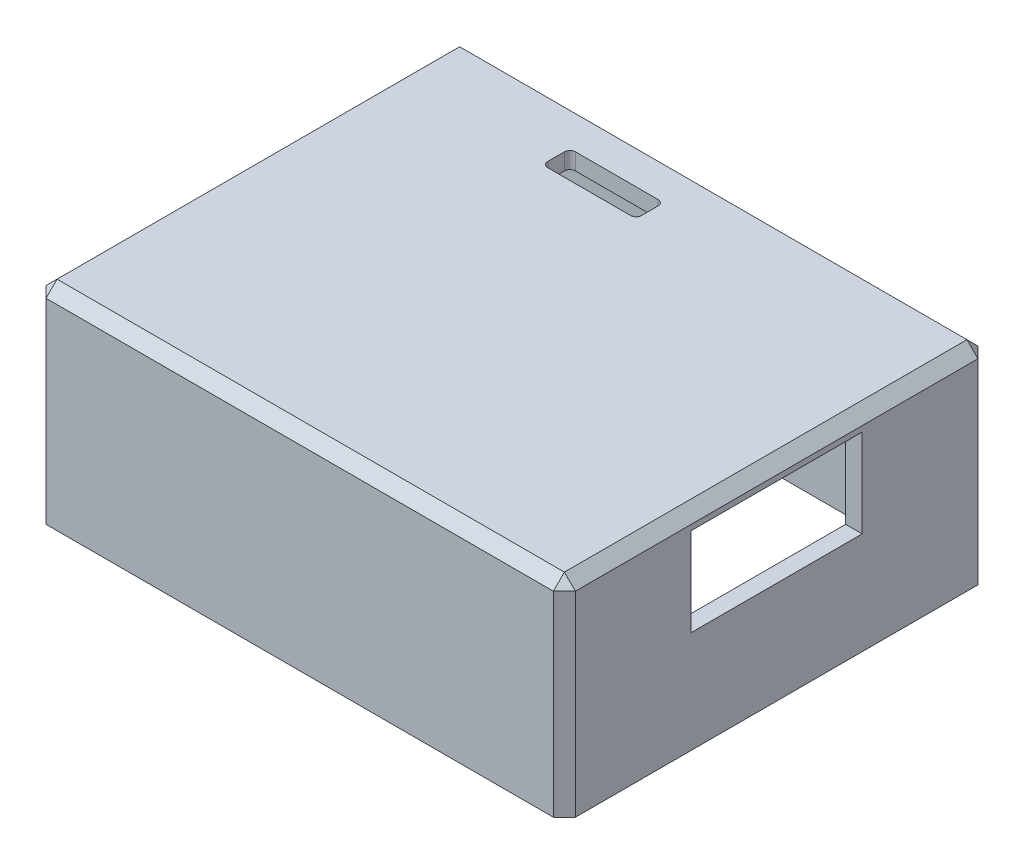
SolidWorks part; units mm, degrees
material "6061 Alloy"
ref_plane "Front Plane" through (0, 0, 0) normal (0, 0, 1) x (1, 0, 0)
ref_plane "Top Plane" through (0, 0, 0) normal (0, 1, 0) x (1, 0, 0)
ref_plane "Right Plane" through (0, 0, 0) normal (1, 0, 0) x (0, 0, -1)
sketch "Sketch1" plane through (0, 0, 0) normal (0, 1, 0) x (1, 0, 0)
  line L1 (0, 0) -> (22.86, 0)
  line L2 (0, 0) -> (0, 18.034)
  line L3 (0, 18.034) -> (22.86, 18.034)
  line L4 (22.86, 0) -> (22.86, 18.034)
  dimension "D1" = 22.86
  dimension "D2" = 18.034
sketch "Sketch2" plane through (0, 0, 0) normal (0, 1, 0) x (1, 0, 0)
  line L1 (-0.762, -0.762) -> (23.622, -0.762)
  line L2 (-0.762, -0.762) -> (-0.762, 18.796)
  line L3 (-0.762, 18.796) -> (23.622, 18.796)
  line L4 (23.622, -0.762) -> (23.622, 18.796)
  line L5 (-0.762, 18.796) -> (23.622, -0.762) construction
  line L6 (0, 0) -> (22.86, 18.034) construction
  line L7 (22.86, 18.034) -> (23.622, 18.034) construction
  line L8 (22.86, 18.034) -> (22.86, 18.796) construction
  line L9 (0, 18.034) -> (22.86, 18.034) construction
  point P10 (11.43, 9.017)
  point P11 (11.43, 9.017)
  dimension "D1" = 0.762
extrude "Boss-Extrude1" add sketch "Sketch2" along normal blind 6.477
extrude "Cut-Extrude1" cut sketch "Sketch1" along normal offset from surface (5.715 mm away) 0.762 up to face at (11.43, 6.477, -9.017)
sketch "Sketch3" plane through (0, 0, 0) normal (0, -1, 0) x (1, 0, 0)
  line L1 (-0.762, -18.796) -> (23.622, -18.796)
  line L2 (-0.762, -18.796) -> (-0.762, 0.762)
  line L3 (-0.762, 0.762) -> (23.622, 0.762)
  line L4 (23.622, -18.796) -> (23.622, 0.762)
  line L5 (0, -18.034) -> (22.86, -18.034)
  line L6 (0, -18.034) -> (0, 0)
  line L7 (0, 0) -> (22.86, 0)
  line L8 (22.86, -18.034) -> (22.86, 0)
extrude "Boss-Extrude2" add sketch "Sketch3" along normal blind 3.048
sketch "Sketch4" plane through (-0.762, 0, 0) normal (-1, 0, 0) x (0, 0, 1)
  line L0 (0.762, -3.048) -> (-18.796, -3.048) construction
  line L1 (-12.192, -6.096) -> (-5.842, -6.096)
  line L2 (-12.192, -6.096) -> (-12.192, 0)
  line L3 (-12.192, 0) -> (-5.842, 0)
  line L4 (-5.842, -6.096) -> (-5.842, 0)
  line L5 (-12.192, -6.096) -> (-5.842, 0) construction
  line L6 (-12.192, 0) -> (-5.842, -6.096) construction
  point P0 (-9.017, -3.048)
  dimension "D1" = 6.35
extrude "Cut-Extrude2" cut sketch "Sketch4" against normal up to next
sketch "Sketch5" plane through (23.622, 0, 0) normal (1, 0, 0) x (0, 0, -1)
  line L0 (9.017, 3.683) -> (-0.762, 3.683) construction
  line L1 (5.08, 5.715) -> (12.954, 5.715)
  line L2 (5.08, 5.715) -> (5.08, 1.651)
  line L3 (5.08, 1.651) -> (12.954, 1.651)
  line L4 (12.954, 5.715) -> (12.954, 1.651)
  line L5 (5.08, 5.715) -> (12.954, 1.651) construction
  line L6 (5.08, 1.651) -> (12.954, 5.715) construction
  line L7 (-0.762, 6.477) -> (-0.762, -3.048) construction
  line L8 (9.017, 3.683) -> (18.796, 3.683) construction
  line L9 (18.796, 6.477) -> (18.796, -3.048) construction
  line L10 (-0.762, 6.477) -> (18.796, 6.477) construction
  point P0 (9.017, 3.683)
  dimension "D1" = 0.762
  dimension "D2" = 7.874
  dimension "D3" = 4.064
extrude "Cut-Extrude3" cut sketch "Sketch5" against normal up to next
chamfer "Chamfer1" distance 0.508 angle 45 8 edges at (11.43, 6.477, -18.796) (23.622, 1.7145, -18.796) (23.622, 6.477, -9.017) (23.622, 1.7145, 0.762) (11.43, 6.477, 0.762) (-0.762, 1.7145, 0.762) (-0.762, 6.477, -9.017) (-0.762, 1.7145, -18.796)
sketch "Sketch6" plane through (0, 6.477, 0) normal (0, 1, 0) x (1, 0, 0)
  line L0 (0, 18.034) -> (22.86, 18.034) construction
  line L1 (6.604, 16.764) -> (10.414, 16.764)
  line L2 (6.35, 16.51) -> (6.35, 15.748)
  line L3 (6.604, 15.494) -> (10.414, 15.494)
  line L4 (10.668, 16.51) -> (10.668, 15.748)
  line L7 (22.86, 18.034) -> (22.86, 12.954) construction
  arc A0 (10.414, 16.764) -> (10.668, 16.51) centre (10.414, 16.51) cw
  arc A1 (10.414, 15.494) -> (10.668, 15.748) centre (10.414, 15.748) ccw
  arc A2 (6.35, 15.748) -> (6.604, 15.494) centre (6.604, 15.748) ccw
  arc A3 (6.604, 16.764) -> (6.35, 16.51) centre (6.604, 16.51) ccw
  point P10 (10.668, 16.764)
  point P13 (10.668, 15.494)
  point P18 (6.35, 16.764)
  dimension "D5" = 0.254
  dimension "D1" = 4.318
  dimension "D2" = 1.27
  dimension "D3" = 12.192
  dimension "D4" = 1.27
extrude "Cut-Extrude4" cut sketch "Sketch6" against normal up to next
sketch "Sketch7" plane through (0, 5.715, 0) normal (0, -1, 0) x (1, 0, 0)
  line L1 (0, -18.034) -> (1.524, -18.034)
  line L2 (0, -18.034) -> (0, -16.51)
  line L3 (0, -16.51) -> (1.524, -16.51)
  line L4 (1.524, -18.034) -> (1.524, -16.51)
  line L5 (0, 0) -> (1.524, 0)
  line L6 (0, 0) -> (0, -1.524)
  line L7 (0, -1.524) -> (1.524, -1.524)
  line L8 (1.524, 0) -> (1.524, -1.524)
  dimension "D1" = 1.524
extrude "Boss-Extrude3" add sketch "Sketch7" along normal up to surface (4.064 mm away) up to face at (23.241, 1.651, -9.017)
